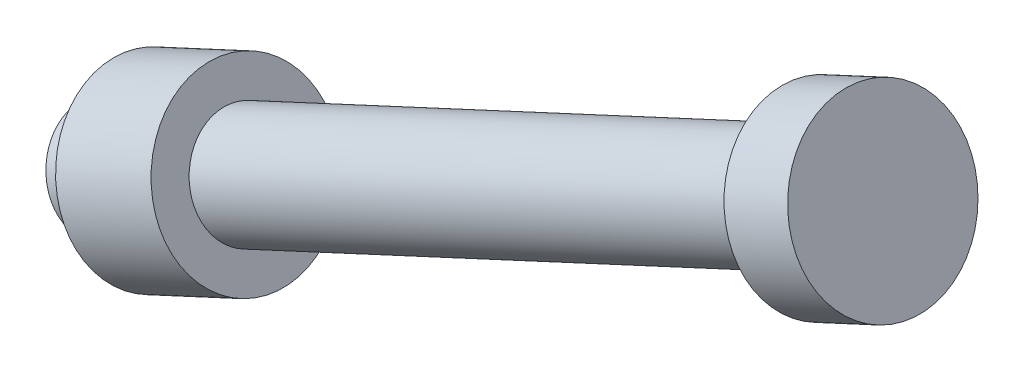
SolidWorks part; units mm, degrees
material "AISI 304"
ref_plane "Alzado" through (0, 0, 0) normal (0, 0, 1) x (1, 0, 0)
ref_plane "Planta" through (0, 0, 0) normal (0, 1, 0) x (1, 0, 0)
ref_plane "Vista lateral" through (0, 0, 0) normal (1, 0, 0) x (0, 0, -1)
sketch3d "Sk_Cabeza"
  line L0 (436.5934, 392.8864, 0) -> (440.2217, 394.5702, 0)
  dimension "D1" = 4
sweep "Cabeza" add path "Sk_Cabeza" circular profile diameter 10 parameters "D3"=10
sketch3d "Sk_Vastago"
  line L0 (395.775, 373.9428, 0) -> (436.5934, 392.8864, 0)
  dimension "D1" = 45
sweep "Vastago" add path "Sk_Vastago" circular profile diameter 6 parameters "D3"=6
sketch3d "Sk_Tuerca"
  line L0 (398.4962, 375.2057, 0) -> (403.9387, 377.7315, 0)
  dimension "D1" = 6
sweep "Tuerca" add path "Sk_Tuerca" circular profile diameter 10 parameters "D3"=10
